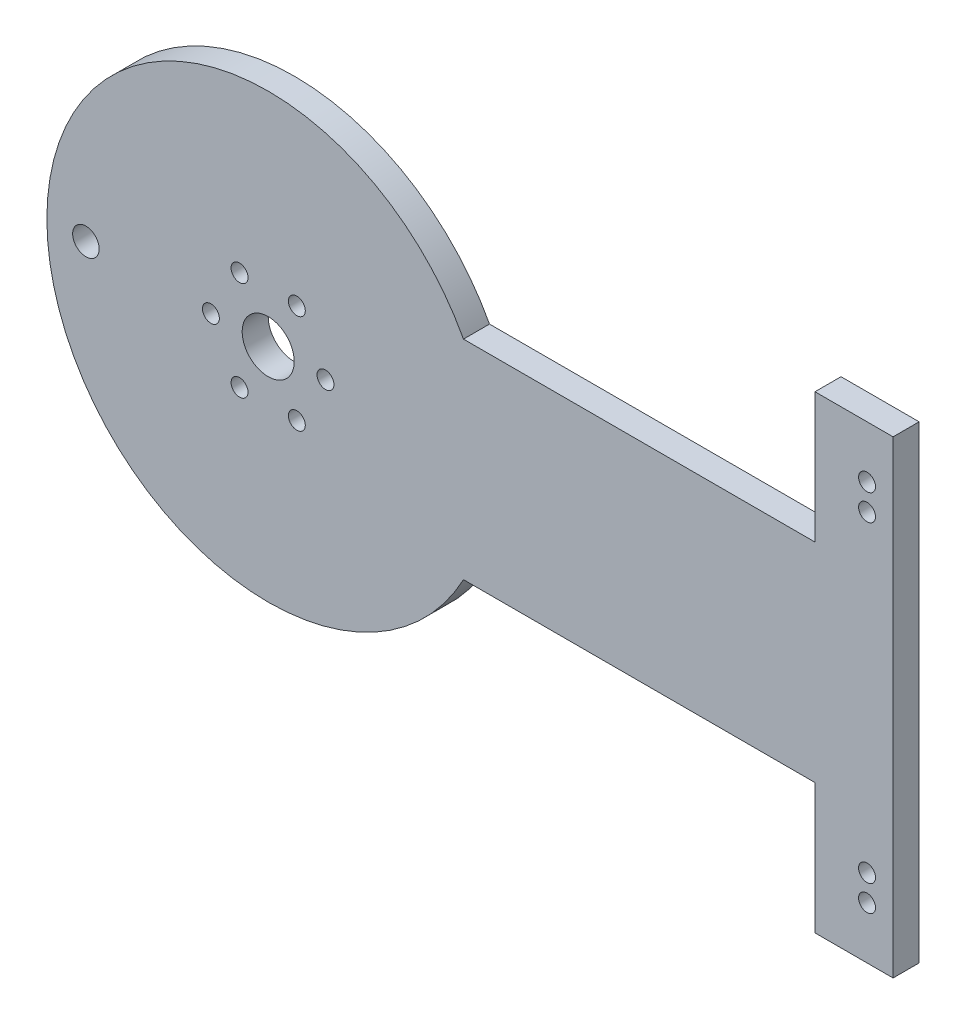
SolidWorks part; units mm, degrees
material "6061-T6 (SS)"
ref_plane "前视基准面" through (0, 0, 0) normal (0, 0, 1) x (1, 0, 0)
ref_plane "上视基准面" through (0, 0, 0) normal (0, 1, 0) x (1, 0, 0)
ref_plane "右视基准面" through (0, 0, 0) normal (1, 0, 0) x (0, 0, -1)
other "Configuration Table"
sketch "草图1" plane through (0, 0, 0) normal (0, 0, 1) x (1, 0, 0)
  circle A0 centre (0, 0) radius 85
extrude "凸台-拉伸1" add sketch "草图1" along normal blind 10
sketch "草图2" plane through (0, 0, 0) normal (0, 0, 1) x (1, 0, 0)
  line L0 (0, -40) -> (240, -40)
  line L1 (240, -40) -> (240, 40)
  line L2 (240, 40) -> (0, 40)
  line L3 (0, 40) -> (0, -40)
extrude "凸台-拉伸2" add sketch "草图2" along normal blind 10
sketch "草图3" plane through (0, 0, 0) normal (0, 0, 1) x (1, 0, 0)
  line L0 (210, -90) -> (240, -90)
  line L1 (240, -90) -> (240, 90)
  line L2 (240, 90) -> (210, 90)
  line L3 (210, 90) -> (210, -90)
extrude "凸台-拉伸3" add sketch "草图3" along normal blind 10
sketch "草图4" plane through (0, 0, 0) normal (0, 0, -1) x (-1, 0, 0)
  circle A0 centre (0, 0) radius 10
  circle A1 centre (-22, 0) radius 3.25
  circle A2 centre (-11, 19.0526) radius 3.25
  circle A3 centre (11, 19.0526) radius 3.25
  circle A4 centre (22, 0) radius 3.25
  circle A5 centre (11, -19.0526) radius 3.25
  circle A6 centre (-11, -19.0526) radius 3.25
  circle A7 centre (-230, -70) radius 3.25
  circle A8 centre (-230, -60) radius 3.25
  circle A9 centre (-230, 60) radius 3.25
  circle A10 centre (-230, 70) radius 3.25
  circle A11 centre (70, 0) radius 5.1
extrude "切除-拉伸1" cut sketch "草图4" against normal blind 11
